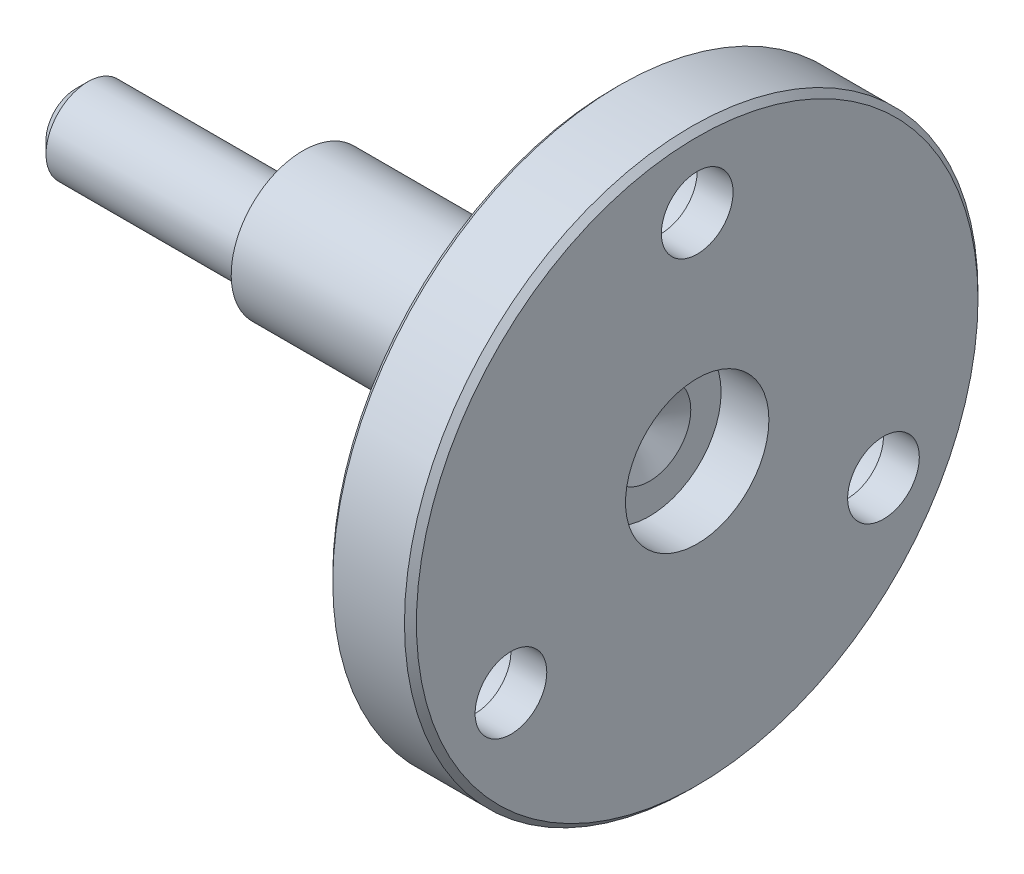
SolidWorks part; units mm, degrees
ref_plane "Face" through (0, 0, 0) normal (0, 0, 1) x (1, 0, 0)
ref_plane "Dessus" through (0, 0, 0) normal (0, 1, 0) x (1, 0, 0)
ref_plane "Droite" through (0, 0, 0) normal (1, 0, 0) x (0, 0, -1)
sketch "Esquisse1" plane through (0, 0, 0) normal (0, 0, 1) x (1, 0, 0)
  line L0 (-33, 0) -> (-33, 6)
  line L1 (-33, 6) -> (-11, 6)
  line L2 (-11, 6) -> (-11, 8)
  line L3 (-11, 8) -> (-10, 8)
  line L4 (-7, 11) -> (-7, 24)
  line L5 (-7, 24) -> (0, 24)
  line L6 (0, 24) -> (0, 6)
  line L7 (0, 6) -> (-4, 6)
  line L8 (-4, 6) -> (-4, 3.4641)
  line L9 (-4, 3.4641) -> (-6, 0)
  line L10 (-6, 0) -> (-33, 0)
  line L11 (0, 0) -> (-42, 0) construction
  arc A0 (-7, 11) -> (-10, 8) centre (-10, 11) cw
  point P16 (-7, 8)
  dimension "D11" = 3
  dimension "D1" = 7
  dimension "D2" = 4
  dimension "D3" = 22
  dimension "D4" = 4
  dimension "D5" = 2
  dimension "D6" = 60
  dimension "D7" = 6
  dimension "D8" = 8
  dimension "D9" = 6
  dimension "D10" = 24
revolve "Base-Révolution" add sketch "Esquisse1" angle 360 about L11
chamfer "Chanfrein2" distance 0.5 angle 45 2 edges at (0, 0, -24) (-7, 0, -24)
sketch "Esquisse2" plane through (0, 0, 0) normal (0, 0, 1) x (1, 0, 0)
  line L0 (-28, 3) -> (-33, 3)
  line L1 (-33, 6) -> (-33, -6) construction
  line L2 (-33, 3) -> (-34, 2)
  line L3 (-34, 2) -> (-51, 2)
  line L4 (-51, 2) -> (-52, 1)
  line L5 (-52, 1) -> (-52, -1.5)
  line L6 (-52, -1.5) -> (-28, -1.5)
  line L7 (-28, -1.5) -> (-28, 3)
  line L8 (-19, -1.5) -> (-53, -1.5) construction
  dimension "D1" = 3.5
  dimension "D2" = 1.5
  dimension "D3" = 45
  dimension "D4" = 45
  dimension "D5" = 19
  dimension "D6" = 1
  dimension "D7" = 1
revolve "Boss.-Révol.1" add sketch "Esquisse2" angle 360 about L8
sketch "Esquisse3" plane through (0, 0, 0) normal (0, 0, 1) x (1, 0, 0)
  line L0 (-12, 18) -> (7, 18) construction
  line L1 (-8, 23) -> (-3, 23)
  line L2 (-3, 23) -> (-3, 21)
  line L3 (-3, 21) -> (4, 21)
  line L4 (4, 21) -> (4, 18)
  line L5 (4, 18) -> (-8, 18)
  line L6 (-8, 18) -> (-8, 23)
  line L7 (-7, 24) -> (-7, -24) construction
  dimension "D1" = 4
  dimension "D2" = 3
  dimension "D3" = 5
  dimension "D4" = 18
revolve "Enlèvement de matière-Révolution2" cut sketch "Esquisse3" angle 360 about L0
pattern_circular "Répétition circulaire1" count 3 every 120 about axis through (0, 0, 0) along (1, 0, 0) of "Enlèvement de matière-Révolution2"
